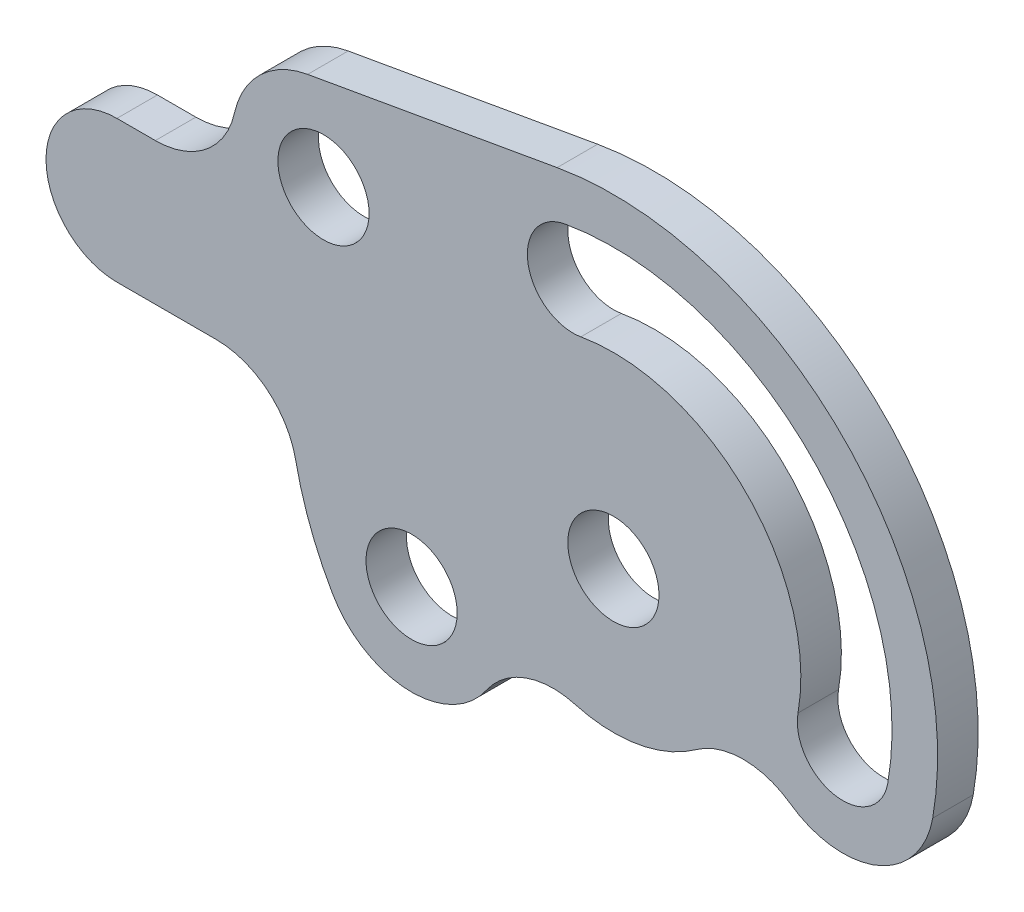
SolidWorks part; units mm, degrees
ref_plane "Front Plane" through (0, 0, 0) normal (0, 0, 1) x (1, 0, 0)
ref_plane "Top Plane" through (0, 0, 0) normal (0, 1, 0) x (1, 0, 0)
ref_plane "Right Plane" through (0, 0, 0) normal (1, 0, 0) x (0, 0, -1)
sketch "Sketch1" plane through (0, 0, 0) normal (0, 0, 1) x (1, 0, 0)
  line L0 (0, 0) -> (9.1281, 0) construction
  line L1 (0, 0) -> (0, 9.1281) construction
  line L2 (0, 0) -> (12.5071, -2.2053) construction
  line L3 (0, 0) -> (-2.2053, 12.5071) construction
  line L4 (-1.5851, 8.9894) -> (-11.3562, 7.2665) construction
  line L5 (0, 5.5562) -> (-22.225, 5.5562) construction
  line L6 (0, 0) -> (-22.225, 0) construction
  line L7 (-22.225, 0) -> (-22.225, 5.5562) construction
  line L8 (-19.4469, 5.5562) -> (-14.492, 5.5562)
  line L9 (-19.4469, 0) -> (-5.5562, 0)
  line L10 (-10.736, 3.7489) -> (-11.9765, 10.7841) construction
  line L11 (-11.9765, 10.7841) -> (-2.2053, 12.5071)
  line L12 (0, 0) -> (-7.9052, -4.5641) construction
  circle A0 centre (0, 0) radius 1.7859
  circle A1 centre (0, 0) radius 5.5562
  circle A2 centre (0, 0) radius 9.1281 construction
  circle A3 centre (-1.5851, 8.9894) radius 1.7859
  circle A4 centre (8.9894, -1.5851) radius 1.7859
  circle A5 centre (-11.3562, 7.2665) radius 1.7859
  circle A6 centre (8.9894, -1.5851) radius 3.5719
  circle A7 centre (-1.5851, 8.9894) radius 3.5719
  circle A8 centre (-11.3562, 7.2665) radius 3.5719
  circle A9 centre (-19.4469, 2.7781) radius 2.7781
  arc A10 (7.2306, -1.275) -> (-1.275, 7.2306) centre (0, 0) ccw
  arc A11 (10.7483, -1.8952) -> (-1.8952, 10.7483) centre (0, 0) ccw
  arc A12 (12.5071, -2.2053) -> (-2.2053, 12.5071) centre (0, 0) ccw
  circle A13 centre (-7.9052, -4.5641) radius 1.7859
  circle A14 centre (-7.9052, -4.5641) radius 3.5719
  arc A15 (12.5071, -2.2053) -> (-10.9985, -6.35) centre (0, 0) cw construction
  arc A16 (-10.9985, -6.35) -> (-12.7, 0) centre (0, 0) cw
  point P24 (-22.225, 2.7781)
  point P35 (-11.3562, 7.2665)
  point P36 (-9.5974, 7.5767)
  point P37 (-3.3439, 8.6793)
  dimension "D4" = 7.1437
  dimension "D5" = 11.1125
  dimension "D6" = 3.5719
  dimension "D1" = 6.35
  dimension "D2" = 10
  dimension "D3" = 10
  dimension "D7" = 22.225
  dimension "D8" = 30
extrude "Boss-Extrude1" add sketch "Sketch1" along normal blind 1.5875 contours A9 | A9 L9 A1 A7 L11 A8 L8 | A8 A5 | A1 A0 | A11 A4 A10 A6 | A6 A10 A7 A1 | A11 A7 A10 A3 | A6 A12 A7 A11 | A14 A13 | A15 A6 A1 A14 | L9 A14 A13
fillet "Fillet1" radius 3.175 4 edges at (5.4718, -0.9648, 0.7937) (-14.492, 5.5562, 0.7937) (-4.8119, -2.7781, 0.7937) (-12.7, 0, 0.7937)
